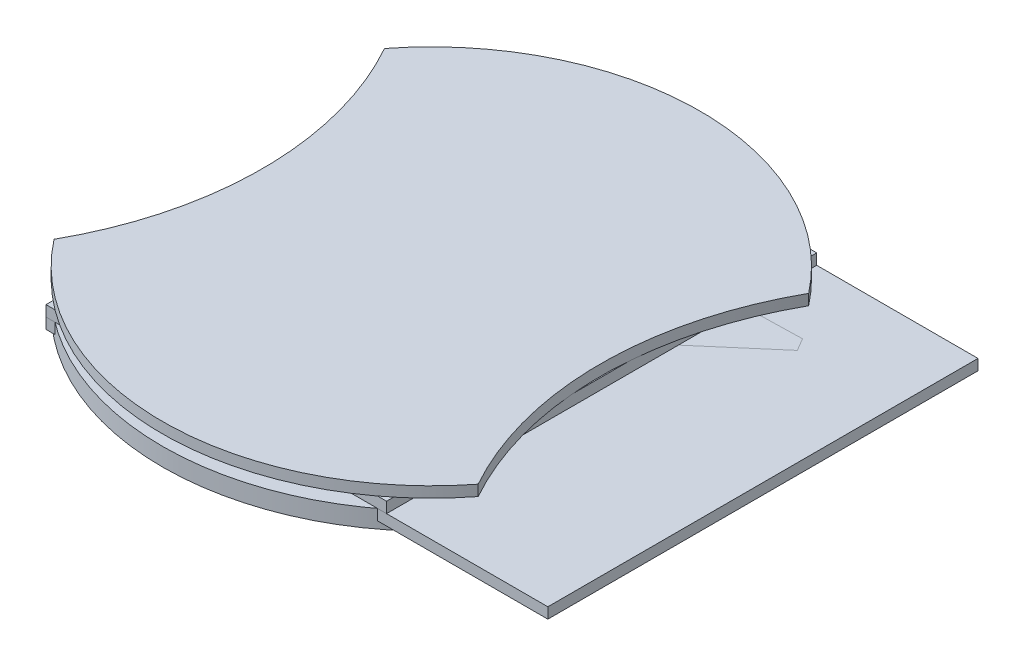
SolidWorks part; units mm, degrees
other "Markup1"
sketch "Sketch33" plane through (-11.66, 9, -138.7946) normal (0, 1, 0) x (1, 0, 0)
other "Markup2"
sketch "Sketch43" plane through (-27.5, 9, 15) normal (-0.0208, 0.9953, 0.0943) x (0.8809, -0.0263, 0.4725)
material "PMMA"
ref_plane "Front Plane" through (0, 0, 0) normal (0, 0, 1) x (1, 0, 0)
ref_plane "Top Plane" through (0, 0, 0) normal (0, 1, 0) x (1, 0, 0)
ref_plane "Right Plane" through (0, 0, 0) normal (1, 0, 0) x (0, 0, -1)
sketch "Sketch1" plane through (0, 0, 0) normal (0, 1, 0) x (1, 0, 0)
  line L1 (0, 0) -> (140, 0)
  line L2 (0, 0) -> (0, 120)
  line L3 (0, 120) -> (140, 120)
  line L4 (140, 0) -> (140, 120)
  dimension "D1" = 120
  dimension "D2" = 140
extrude "Compact" add sketch "Sketch1" along normal blind 3
sketch "Center Guide" plane through (0, 0, 0) normal (-1, 0, 0) x (0, 0, 1)
  line L0 (-60, 0) -> (-60, -3) construction
  line L1 (-120, 0) -> (0, 0) construction
  line L2 (-60, 3) -> (-60, 16.3)
  line L3 (-120, 3) -> (0, 3) construction
  line L4 (-60, 3) -> (-60, 24.5)
  circle A0 centre (-60, -3) radius 10.0584
  circle A1 centre (-60, 16.3) radius 5.9898
  circle A2 centre (-60, 24.5) radius 8.3651
  dimension "D2" = 13.3
  dimension "D3" = 21.5
  dimension "D1" = 3
sketch "Sketch4" plane through (0, 3, 0) normal (0, 1, 0) x (1, 0, 0)
  line L0 (0, 0) -> (140, 0) construction
  line L1 (0, 120) -> (95, 120)
  line L2 (0, 120) -> (0, 0)
  line L3 (0, 0) -> (95, 0)
  line L4 (95, 120) -> (95, 0)
  dimension "D1" = 95
extrude "SuperCompact" add sketch "Sketch4" along normal blind 3 separate body
sketch "Sketch5" plane through (0, 6, 0) normal (0, 1, 0) x (1, 0, 0)
  line L0 (47.5, 120) -> (47.5, 103.0921) construction
  line L1 (95, 120) -> (0, 120) construction
  line L2 (0, 60) -> (21.8037, 60) construction
  line L3 (0, 120) -> (0, 0) construction
  line L4 (70, 120) -> (70, 93.0513) construction
  line L5 (140, 120) -> (0, 120) construction
  circle A0 centre (5, 115) radius 1.5
  circle A1 centre (90, 115) radius 1.5
  circle A2 centre (90, 5) radius 1.5
  circle A3 centre (5, 5) radius 1.5
  circle A4 centre (135, 5) radius 1.5
  circle A5 centre (135, 115) radius 1.5
  dimension "D1" = 3
  dimension "D2" = 5
  dimension "D3" = 5
sketch "Sketch7" plane through (0, 6, 0) normal (0, 1, 0) x (1, 0, 0)
  line L0 (47.5, 120) -> (47.5, 0) construction
  line L1 (95, 120) -> (0, 120) construction
  line L2 (0, 0) -> (95, 0) construction
  circle A0 centre (47.5, 60) radius 75
  dimension "D1" = 150
extrude "Apple Base" add sketch "Sketch7" along normal blind 3 separate body
sketch "Sketch8" plane through (0, 9, 0) normal (0, 1, 0) x (1, 0, 0)
  line L1 (0, 120) -> (0, 0) construction
  line L2 (0, 100.6202) -> (0, 77.7186) construction
  line L3 (47.5, 135) -> (47.5, 108.0988) construction
  line L7 (-27.5, 60) -> (-27.5, 91.6393) construction
  arc A1 (-11.66, 106.0987) -> (-11.66, 13.9013) centre (-94.1268, 60) cw
  circle A2 centre (47.5, 60) radius 75 construction
  circle A3 centre (47.5, 60) radius 75
  arc A4 (-11.66, 106.0987) -> (-11.66, 13.9013) centre (47.5, 60) ccw
  arc A5 (106.66, 106.0987) -> (106.66, 13.9013) centre (189.1268, 60) ccw
  arc A6 (106.66, 106.0987) -> (106.66, 13.9013) centre (47.5, 60) cw
  dimension "D2" = 0
extrude "SideCuts" cut sketch "Sketch8" against normal through all
sketch "Sketch9" plane through (0, 6, 0) normal (0, -1, 0) x (1, 0, 0)
  arc A4 (106.66, -13.9013) -> (-11.66, -13.9013) centre (47.5, -60) ccw
  arc A5 (-11.66, -106.0987) -> (-11.66, -13.9013) centre (-94.1268, -60) ccw
  arc A6 (-11.66, -106.0987) -> (106.66, -106.0987) centre (47.5, -60) ccw
  arc A7 (106.66, -13.9013) -> (106.66, -106.0987) centre (189.1268, -60) ccw
  arc A8 (106.66, -13.9013) -> (-11.66, -13.9013) centre (47.5, -60) ccw
  arc A9 (-11.66, -106.0987) -> (-11.66, -13.9013) centre (-94.1268, -60) ccw
  arc A10 (-11.66, -106.0987) -> (106.66, -106.0987) centre (47.5, -60) ccw
  arc A11 (106.66, -13.9013) -> (106.66, -106.0987) centre (189.1268, -60) ccw
  dimension "D1" = 0
extrude "Apple_Base" add sketch "Sketch9" along normal blind 3 separate body
sketch "Sketch10" plane through (0, 6, 0) normal (0, 1, 0) x (1, 0, 0)
  line L0 (-11.66, 106.0987) -> (-11.66, 13.9013)
  line L1 (106.66, 106.0987) -> (106.66, 13.9013)
  arc A4 (106.66, 106.0987) -> (106.66, 13.9013) centre (189.1268, 60) ccw
  arc A5 (106.66, 106.0987) -> (-11.66, 106.0987) centre (47.5, 60) ccw
  arc A6 (-11.66, 13.9013) -> (-11.66, 106.0987) centre (-94.1268, 60) ccw
  arc A7 (-11.66, 13.9013) -> (106.66, 13.9013) centre (47.5, 60) ccw
  arc A8 (106.66, 106.0987) -> (106.66, 13.9013) centre (189.1268, 60) ccw
  arc A10 (-11.66, 13.9013) -> (-11.66, 106.0987) centre (-94.1268, 60) ccw
  dimension "D1" = 0
extrude "Boss-Extrude4" add sketch "Sketch10" against normal blind 3
sketch "Sketch11" plane through (0, 0, 0) normal (0, 0, 1) x (1, 0, 0)
  line L0 (-11.66, 6) -> (106.66, 6)
  line L1 (47.5, 6) -> (47.5, 18.0317)
fillet "Base_Plate_Fillet" radius 0.001 12 edges at (106.66, 6, -60) (106.66, 3, -60) (-11.66, 6, -60) (-11.66, 3, -60) (47.5, 6, -135) (47.5, 3, -135) (47.5, 6, 15) (47.5, 3, 15) (106.66, 4.5, -106.0987) (-11.66, 4.5, -106.0987) (-11.66, 4.5, -13.9013) (106.66, 4.5, -13.9013)
sketch "Sketch12" plane through (0, 6, 0) normal (0, 1, 0) x (1, 0, 0)
  line L0 (-11.659, 106.0984) -> (-11.659, 13.9016) construction
  line L1 (106.659, 13.9016) -> (106.659, 106.0984) construction
  line L2 (-4.6496, 43.9016) -> (-4.6496, 76.9016) construction
  line L3 (47.5, 134.999) -> (47.5, 105.9694) construction
  circle A0 centre (-4.6496, 43.9016) radius 2.5
  circle A1 centre (-4.6496, 76.9016) radius 2.5
  arc A2 (106.659, 106.0984) -> (-11.659, 106.0984) centre (47.5, 60) ccw construction
  circle A6 centre (99.659, 75.8016) radius 2.5
  circle A7 centre (99.659, 42.8016) radius 2.5
  dimension "D3" = 5
  dimension "D5" = 5
  dimension "D1" = 30
  dimension "D2" = 7.0094
  dimension "D4" = 33
  dimension "D6" = 33
  dimension "D7" = 28.9
  dimension "D8" = 7
extrude "Base_Screw_Holes" [suppressed] cut sketch "Sketch12" against normal blind 14
sketch "Old_Motor_Mounts" plane through (0, 6, 0) normal (0, 1, 0) x (1, 0, 0)
  line L0 (3.341, 134.7458) -> (3.341, -10.3072) construction
  line L1 (47.5, 134.999) -> (47.5, -14.999) construction
  line L2 (-11.659, 106.0984) -> (-11.659, 13.9016) construction
  line L3 (7.341, 70.6984) -> (7.341, 106.6984)
  line L4 (3.341, 70.6984) -> (3.341, 106.6984)
  line L5 (3.341, 106.6984) -> (7.341, 106.6984)
  line L6 (3.341, 70.6984) -> (7.341, 70.6984)
  line L11 (47.5, 60) -> (73.1154, 60) construction
  line L12 (91.659, 49.3016) -> (87.16, 49.4734)
  line L13 (87.16, 49.4734) -> (87.6619, 13.4542)
  line L14 (91.659, 13.3016) -> (87.6619, 13.4542)
  line L15 (91.659, 49.3016) -> (91.659, 13.3016)
  line L16 (106.659, 13.9016) -> (106.659, 106.0984) construction
  arc A0 (106.659, 106.0984) -> (-11.659, 106.0984) centre (47.5, 60) ccw construction
  arc A1 (-11.659, 13.9016) -> (106.659, 13.9016) centre (47.5, 60) ccw construction
  point P12 (3.341, 88.6984)
  point P16 (91.659, 31.3016)
  dimension "D1" = 15
  dimension "D2" = 17.4
  dimension "D3" = 36
  dimension "D5" = 36
  dimension "D6" = 15
  dimension "D7" = 4
  dimension "D8" = 17.4
  dimension "D4" = 4
ref_plane "MidPlane" through (0, 0, -60) normal (0, 0, 1) x (1, 0, 0)
sketch "Sketch24" plane through (0, 6, 0) normal (0, 1, 0) x (1, 0, 0)
  line L0 (-3.66, 114.8421) -> (-3.66, 5.1579)
  line L2 (-11.66, 13.9016) -> (-11.66, 106.0984) construction
  line L3 (47.5, 134.999) -> (47.5, 105.1076) construction
  line L4 (98.66, 114.8421) -> (98.66, 5.1579)
  line L5 (106.66, 106.0984) -> (106.66, 13.9016) construction
  line L6 (106.66, 106.0984) -> (106.66, 13.9016)
  line L7 (-11.66, 13.9016) -> (-11.66, 106.0984)
  arc A0 (106.659, 106.0984) -> (-11.659, 106.0984) centre (47.5, 60) ccw construction
  arc A1 (-11.6598, 106.099) -> (-11.66, 106.0984) centre (-11.659, 106.0984) ccw construction
  arc A2 (106.6598, 106.099) -> (-11.6598, 106.099) centre (47.5, 60) ccw construction
  arc A3 (106.66, 106.0984) -> (106.6598, 106.099) centre (106.659, 106.0984) ccw construction
  arc A4 (106.6598, 13.901) -> (106.66, 13.9016) centre (106.659, 13.9016) ccw construction
  arc A5 (-11.6598, 13.901) -> (106.6598, 13.901) centre (47.5, 60) ccw construction
  arc A6 (-11.66, 13.9016) -> (-11.6598, 13.901) centre (-11.659, 13.9016) ccw construction
  arc A7 (-11.6598, 106.099) -> (-11.66, 106.0984) centre (-11.659, 106.0984) ccw
  arc A8 (106.6598, 106.099) -> (98.66, 114.8421) centre (47.5, 60) ccw
  arc A9 (106.66, 106.0984) -> (106.6598, 106.099) centre (106.659, 106.0984) ccw
  arc A10 (106.6598, 13.901) -> (106.66, 13.9016) centre (106.659, 13.9016) ccw
  arc A11 (-11.6598, 13.901) -> (-3.66, 5.1579) centre (47.5, 60) ccw
  arc A12 (-11.66, 13.9016) -> (-11.6598, 13.901) centre (-11.659, 13.9016) ccw
  arc A13 (98.66, 5.1579) -> (106.6598, 13.901) centre (47.5, 60) ccw
  arc A14 (-3.66, 114.8421) -> (-11.6598, 106.099) centre (47.5, 60) ccw
  dimension "D1" = 8
  dimension "D2" = 8
extrude "Cut-Extrude3" [suppressed] cut sketch "Sketch24" against normal blind 6
sketch "Sketch25" plane through (0, 6, 0) normal (0, 1, 0) x (1, 0, 0)
  line L0 (-11.659, 106.0974) -> (-11.659, 111.0974)
  line L1 (47.5, 135) -> (47.5, 124.3332) construction
  line L2 (106.659, 106.0974) -> (106.659, 111.0974)
  line L3 (-11.66, 60) -> (55.4784, 60) construction
  line L4 (-11.66, 13.9016) -> (-11.66, 106.0984) construction
  line L5 (106.659, 13.9026) -> (106.659, 8.9026)
  line L6 (-11.659, 13.9026) -> (-11.659, 8.9026)
  arc A0 (-11.6598, 106.099) -> (-11.66, 106.0984) centre (-11.659, 106.0984) ccw construction
  arc A1 (106.6598, 106.099) -> (-11.6598, 106.099) centre (47.5, 60) ccw construction
  arc A2 (-11.659, 111.0974) -> (106.659, 111.0974) centre (47.5, 61.7666) cw
  arc A3 (-11.659, 106.0974) -> (106.659, 106.0974) centre (47.5, 56.7666) cw
  arc A4 (-11.659, 13.9026) -> (106.659, 13.9026) centre (47.5, 63.2334) ccw
  arc A5 (-11.659, 8.9026) -> (106.659, 8.9026) centre (47.5, 58.2334) ccw
  arc M15 (106.659, 106.0984) -> (-11.659, 106.0984) centre (47.5, 60) ccw
  arc M17 (-11.659, 13.9016) -> (106.659, 13.9016) centre (47.5, 60) ccw
  dimension "D1" = 5
extrude "Top Bottom extensions" add sketch "Sketch25" against normal blind 3 contours L6 A5 L5 A4 M17 | L0 A3 L2 A2 M15
sketch "Sketch28" plane through (0, 6, 0) normal (0, 1, 0) x (1, 0, 0)
  line L0 (-11.659, 60) -> (106.659, 60) construction
  line L1 (37.5, 6) -> (57.5, 6) construction
  line L2 (37.5, 6) -> (37.5, -14) construction
  line L3 (37.5, -14) -> (57.5, -14) construction
  line L4 (57.5, 6) -> (57.5, -14) construction
  line L5 (-11.659, 106.0984) -> (-11.659, 13.9016) construction
  line L6 (106.659, 13.9016) -> (106.659, 106.0984) construction
  line L7 (47.5, 6) -> (47.5, -4) construction
  line L8 (47.5, -4) -> (37.5, -4) construction
  circle A0 centre (41.5, 2) radius 1.75
  circle A1 centre (41.5, -10) radius 1.75
  circle A2 centre (53.5, -10) radius 1.75
  circle A3 centre (53.5, 2) radius 1.75
  circle A4 centre (53.5, 130) radius 1.75
  circle A5 centre (53.5, 118) radius 1.75
  circle A6 centre (41.5, 118) radius 1.75
  circle A7 centre (41.5, 130) radius 1.75
  point P30 (47.5, 60)
  dimension "D4" = 3.5
  dimension "D1" = 20
  dimension "D2" = 20
  dimension "D3" = 54
  dimension "D5" = 4
  dimension "D6" = 4
extrude "RodHolder holes" [suppressed] cut sketch "Sketch28" against normal blind 11
sketch "Sketch29" plane through (0, 6, 0) normal (0, 1, 0) x (1, 0, 0)
  line L0 (47.5, 138.7946) -> (47.5, -18.7946) construction
  line L5 (47.5, 60) -> (59.8359, 60) construction
  line L7 (11.25, 7.85) -> (83.75, 7.85) construction
  line L8 (11.25, 7.85) -> (11.25, 112.15) construction
  line L9 (11.25, 112.15) -> (83.75, 112.15) construction
  line L10 (83.75, 7.85) -> (83.75, 112.15) construction
  line L11 (11.25, 7.85) -> (83.75, 112.15) construction
  line L12 (11.25, 112.15) -> (83.75, 7.85) construction
  arc A5 (106.659, 111.0974) -> (-11.659, 111.0974) centre (47.5, 61.7666) ccw construction
  arc A6 (-11.659, 8.9026) -> (106.659, 8.9026) centre (47.5, 58.2334) ccw construction
  circle A7 centre (11.25, 112.15) radius 1.5
  circle A8 centre (83.75, 112.15) radius 1.5
  circle A9 centre (83.75, 7.85) radius 1.5
  circle A10 centre (11.25, 7.85) radius 1.5
  point P9 (47.5, 60)
  dimension "D1" = 104.3
  dimension "D3" = 3
  dimension "D2" = 72.5
extrude "Height extender holes" [suppressed] cut sketch "Sketch29" against normal blind 10
sketch "Sketch31" plane through (0, 6, 0) normal (0, 1, 0) x (1, 0, 0)
  line L0 (-11.659, 60) -> (106.659, 60) construction
  line L1 (-11.659, 106.0984) -> (-11.659, 13.9016) construction
  line L2 (106.659, 13.9016) -> (106.659, 106.0984) construction
  line L3 (47.5, 138.7946) -> (47.5, -18.7946) construction
  line L4 (47.5, 112) -> (72.8768, 112) construction
  arc A0 (106.659, 111.0974) -> (-11.659, 111.0974) centre (47.5, 61.7666) ccw construction
  arc A1 (-11.659, 8.9026) -> (106.659, 8.9026) centre (47.5, 58.2334) ccw construction
  circle A2 centre (47.5, 122) radius 10
  circle A3 centre (47.5, 122) radius 8
  circle A4 centre (47.5, 122) radius 15
  dimension "D1" = 20
  dimension "D3" = 2
  dimension "D4" = 30
  dimension "D2" = 52
sketch "Sketch34" plane through (0, 3, 0) normal (0, -1, 0) x (-1, 0, 0)
  line L0 (-47.5, -18.7946) -> (-47.5, 138.7946) construction
  arc A0 (-106.659, 8.9026) -> (11.659, 8.9026) centre (-47.5, 58.2334) ccw construction
  arc A1 (11.659, 111.0974) -> (-106.659, 111.0974) centre (-47.5, 61.7666) ccw construction
  circle A2 centre (-47.5, 60) radius 12.859
sketch "Sketch35" plane through (0, 3, 0) normal (0, -1, 0) x (1, 0, 0)
  line L0 (47.5, 18.7946) -> (47.5, -138.7946) construction
  line L1 (6.25, -114.85) -> (88.75, -114.85) construction
  line L2 (47.5, -60) -> (61.5955, -60) construction
  line L3 (7.5, -3.9) -> (7.5, -116.1) construction
  line L4 (6.25, -5.15) -> (86.25, -5.15) construction
  line L5 (87.5, -3.9) -> (87.5, -116.1) construction
  line L6 (7.5, 18.7946) -> (7.5, -138.7946) construction
  line L7 (87.5, 18.7946) -> (87.5, -138.7946) construction
  arc A0 (106.659, -8.9026) -> (-11.659, -8.9026) centre (47.5, -58.2334) ccw construction
  arc A1 (-11.659, -111.0974) -> (106.659, -111.0974) centre (47.5, -61.7666) ccw construction
  circle A2 centre (7.5, -5.15) radius 1.25
  circle A3 centre (87.5, -5.15) radius 1.25
  circle A4 centre (87.5, -114.85) radius 1.25
  circle A5 centre (7.5, -114.85) radius 1.25
  dimension "D1" = 40
  dimension "D3" = 2.5
  dimension "D4" = 80
  dimension "D5" = 112.2
  dimension "D2" = 40
extrude "SpacerHoles" cut sketch "Sketch35" against normal blind 10
sketch "Sketch37" plane through (0, 3, 0) normal (0, -1, 0) x (1, 0, 0)
sketch "Sketch38" plane through (0, 3, 0) normal (0, -1, 0) x (1, 0, 0)
  line L0 (-11.659, -60) -> (-6.659, -60)
  line L1 (-11.659, -13.9016) -> (-11.659, -106.0984) construction
  line L2 (-6.659, -60) -> (-6.659, 24.7024)
  line L3 (101.659, -60) -> (106.659, -60)
  line L4 (106.659, -106.0984) -> (106.659, -13.9016) construction
  line L5 (-6.659, 24.7024) -> (101.659, 24.7024)
  line L6 (101.659, 24.7024) -> (101.659, -143.8435)
  line L7 (101.659, -143.8435) -> (-6.659, -143.8435)
  line L8 (-6.659, -143.8435) -> (-6.659, -60)
  line L9 (47.5, 37.0501) -> (120.3723, 37.0501)
  line L10 (120.3723, 37.0501) -> (120.3723, -158.6018)
  line L11 (120.3723, -158.6018) -> (-29.1775, -158.6018)
  line L12 (-29.1775, -158.6018) -> (-29.1775, 37.0501)
  line L13 (-29.1775, 37.0501) -> (47.5, 37.0501)
  line M7 (106.659, -106.0984) -> (106.659, -13.9016)
  line M8 (106.659, -13.9016) -> (106.659, -8.9026)
  arc M9 (106.659, -8.9026) -> (-11.659, -8.9026) centre (47.5, -58.2334) ccw
  line M10 (-11.659, -8.9026) -> (-11.659, -13.9016)
  line M11 (-11.659, -13.9016) -> (-11.659, -106.0984)
  line M12 (-11.659, -106.0984) -> (-11.659, -111.0974)
  arc M13 (-11.659, -111.0974) -> (106.659, -111.0974) centre (47.5, -61.7666) ccw
  line M14 (106.659, -111.0974) -> (106.659, -106.0984)
  dimension "D1" = 5
  dimension "D2" = 5
extrude "Cut-Extrude4" cut sketch "Sketch38" against normal blind 10 contours L13 L12 L11 L10 L9 L7 L8 L2 L5 L6 M13 M12 M11 M10 M9 M8 M7 M14 | L6 L3 M9 M7 M8 | L0 L2 M9 M10 M11 | L8 L0 M13 M11 M12 | L3 L6 M13 M14 M7
sketch "Sketch39" plane through (0, 3, 0) normal (0, -1, 0) x (1, 0, 0)
  line L0 (47.5, 18.7946) -> (47.5, -81.8228) construction
  line L2 (101.659, -60) -> (38.5892, -60) construction
  line L3 (101.659, -3.4601) -> (101.659, -116.5399) construction
  arc A1 (101.659, -3.4601) -> (-6.659, -3.4601) centre (47.5, -58.2334) ccw construction
  circle A2 centre (47.5, -60) radius 75
  circle A3 centre (87.5, -5.15) radius 1.25
  circle A4 centre (7.5, -5.15) radius 1.25
  circle A5 centre (7.5, -114.85) radius 1.25
  circle A6 centre (87.5, -114.85) radius 1.25
  dimension "D1" = 150
extrude "Boss-Extrude5" add sketch "Sketch39" along normal blind 5
sketch "Sketch40" plane through (101.659, 0, 0) normal (1, 0, 0) x (0, 0, -1)
  line L0 (3.4601, 3) -> (-22.7338, 3)
  line L1 (-22.7338, 3) -> (-22.7338, 8.214)
  line L2 (-22.7338, 8.214) -> (147.503, 8.214)
  line L3 (147.503, 8.214) -> (147.503, 3)
  line L4 (147.503, 3) -> (3.4601, 3)
extrude "Cut-Extrude5" cut sketch "Sketch40" against normal blind 150
sketch "Sketch41" plane through (0, 3, 0) normal (0, 1, 0) x (1, 0, 0)
  line L0 (47.5, 60) -> (97.5, 60)
  circle A3 centre (47.5, 60) radius 8.4
  circle A4 centre (97.5, 60) radius 8.5
  dimension "D2" = 50
  dimension "D6" = 16.8
  dimension "D4" = 17
extrude "Cut-Extrude6" cut sketch "Sketch41" against normal blind 10
sketch "Sketch44" plane through (0, 3, 0) normal (0, 1, 0) x (1, 0, 0)
  line L0 (47.5, 60) -> (107.5, 60)
  circle A0 centre (107.5, 60) radius 8.4
  dimension "D2" = 16.8
  dimension "D1" = 60
extrude "Cut-Extrude7" cut sketch "Sketch44" against normal blind 10
sketch "Sketch45" plane through (0, -2, 0) normal (0, -1, 0) x (1, 0, 0)
  line L0 (47.5, -60) -> (47.5, -41.4206) construction
  line L1 (47.5, -60) -> (76.9611, -19.6014)
  line L2 (47.5, -60) -> (69.1497, -60) construction
  circle A0 centre (76.9611, -19.6014) radius 1.5
  circle A1 centre (18.0389, -19.6014) radius 1.5
  circle A2 centre (76.9611, -100.3986) radius 1.5
  circle A3 centre (18.0389, -100.3986) radius 1.5
  dimension "D2" = 3
  dimension "D1" = 50
extrude "Cut-Extrude8" cut sketch "Sketch45" against normal blind 12 contours A2 | A3 | A1
sketch "Sketch46" plane through (0, -2, 0) normal (0, -1, 0) x (1, 0, 0)
  line L0 (18.0389, -19.6014) -> (18.0389, -100.3986) construction
  line L1 (47.5, -60) -> (47.5, -35.46) construction
  line L2 (76.9611, -19.6014) -> (76.9611, -100.3986) construction
  circle A0 centre (76.9611, -19.6014) radius 1.5
  circle A1 centre (18.0389, -19.6014) radius 1.5 construction
extrude "Cut-Extrude9" cut sketch "Sketch46" against normal blind 10
sketch "Sketch47" plane through (0, 3, 0) normal (0, 1, 0) x (1, 0, 0)
  point P0 (47.5, 60)
  point P1 (7.5, 114.85)
  point P4 (87.5, 114.85)
  point P5 (7.5, 5.15)
  point P9 (87.5, 5.15)
  dimension "D1" = 54.85
  dimension "D2" = 40
  dimension "D3" = 67.8861
  dimension "D4" = 40
  dimension "D5" = 67.8861
sketch "Sketch48" plane through (0, 3, 0) normal (0, 1, 0) x (1, 0, 0)
  line L0 (47.5, 60) -> (-2.5, 60)
  line L1 (-2.5, 60) -> (-2.5, 121.8193)
  line L2 (-2.5, 60) -> (-2.5, -6.9968)
  arc A0 (-2.5, 121.8193) -> (-2.5, -6.9968) centre (36.3693, 57.4113) ccw
  circle M8 centre (47.5, 60) radius 75
  dimension "D1" = 50
extrude "Cut-Extrude10" cut sketch "Sketch48" against normal blind 10 contours L2 L1 M8
sketch "Sketch49" plane through (0, 3, 0) normal (0, 1, 0) x (1, 0, 0)
  line L0 (47.5, 135) -> (47.5, 127)
  line L7 (62.8623, 118) -> (81.041, 118)
  line L8 (32.1377, 118) -> (13.959, 118)
  line L9 (62.8623, 2) -> (81.041, 2)
  line L10 (32.1377, 2) -> (13.959, 2)
  circle A2 centre (47.5, 60) radius 75 construction
  arc A3 (13.959, 2) -> (81.041, 2) centre (47.5, 60) ccw
  arc A4 (32.1377, 2) -> (62.8623, 2) centre (47.5, 60) ccw
  arc A5 (62.8623, 118) -> (32.1377, 118) centre (47.5, 60) ccw
  arc A6 (81.041, 118) -> (13.959, 118) centre (47.5, 60) ccw
  dimension "D2" = 134
  dimension "D3" = 120
  dimension "D1" = 8
extrude "Cut-Extrude11" cut sketch "Sketch49" against normal blind 10 contours L7 A6 L8 A5 | A4 L10 A3 L9
